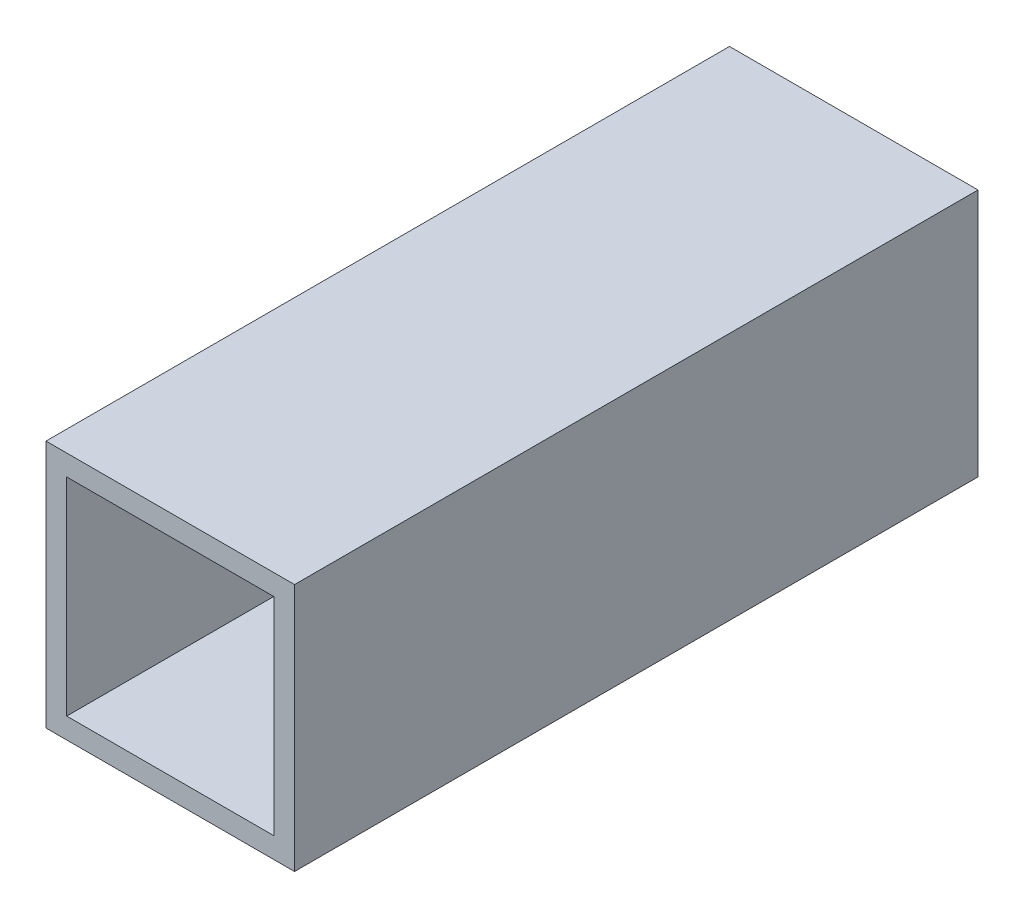
SolidWorks part; units mm, degrees
ref_plane "前视基准面" through (0, 0, 0) normal (0, 0, 1) x (1, 0, 0)
ref_plane "上视基准面" through (0, 0, 0) normal (0, 1, 0) x (1, 0, 0)
ref_plane "右视基准面" through (0, 0, 0) normal (1, 0, 0) x (0, 0, -1)
sketch "草图1" plane through (0, 0, 0) normal (0, 0, 1) x (1, 0, 0)
  line L0 (-12, 12) -> (12, 12)
  line L1 (-10, 10) -> (10, 10)
  line L2 (-10, 10) -> (-10, -10)
  line L3 (-10, -10) -> (10, -10)
  line L4 (10, 10) -> (10, -10)
  line L5 (-10, 10) -> (10, -10) construction
  line L6 (-10, -10) -> (10, 10) construction
  line L7 (12, 12) -> (12, -12)
  line L8 (-12, -12) -> (12, -12)
  line L9 (-12, 12) -> (-12, -12)
  point P0 (0, 0)
  dimension "D1" = 20
  dimension "D2" = 20
  dimension "D3" = 2
extrude "凸台-拉伸1" add sketch "草图1" along normal mid plane 66
